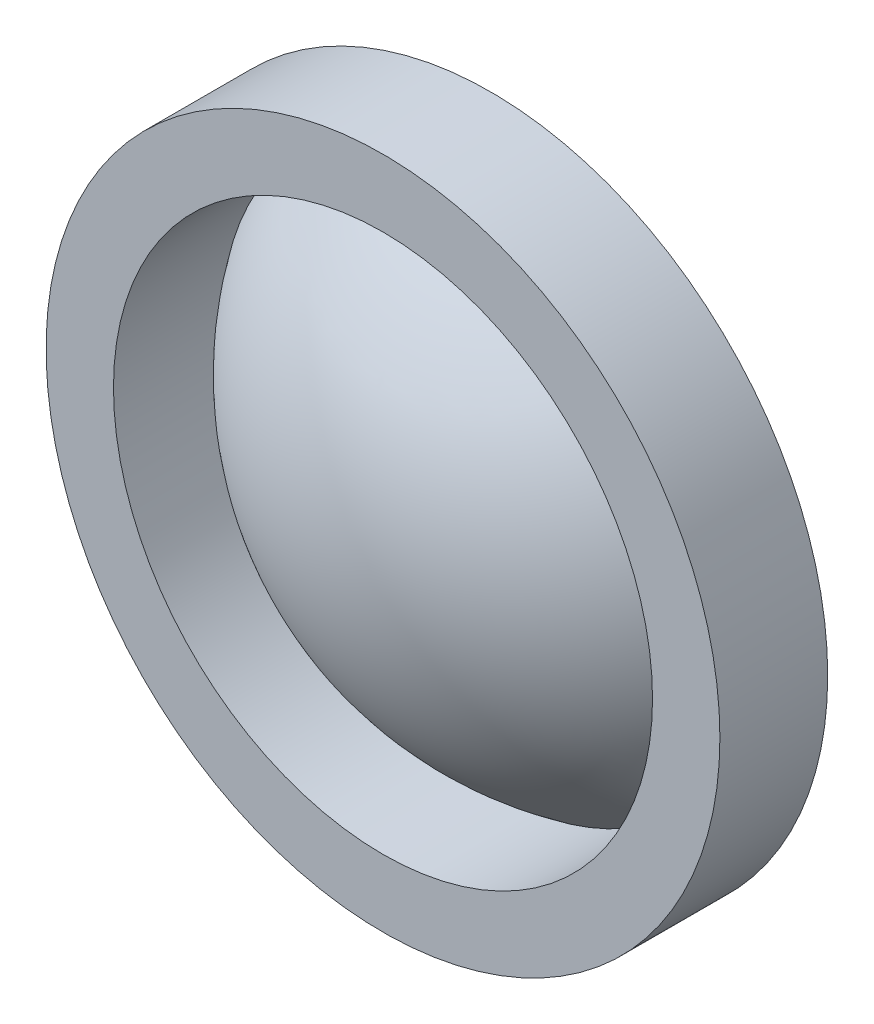
SolidWorks part; units mm, degrees
material "6061 Alloy"
ref_plane "Front" through (0, 0, 0) normal (0, 0, 1) x (1, 0, 0)
ref_plane "Top" through (0, 0, 0) normal (0, 1, 0) x (1, 0, 0)
ref_plane "Right" through (0, 0, 0) normal (1, 0, 0) x (0, 0, -1)
sketch "Sketch2" plane through (0, 0, 0) normal (0, 0, 1) x (1, 0, 0)
  circle A0 centre (0, 0) radius 1000
  circle A1 centre (0, 0) radius 1250
  dimension "D1" = 2000
  dimension "D2" = 2500
extrude "Boss-Extrude1" add sketch "Sketch2" along normal blind 400
sketch "Sketch3" plane through (0, 0, 0) normal (1, 0, 0) x (0, 0, -1)
  line L2 (0, 0) -> (0, -1000)
  line L3 (0, 0) -> (-528.7511, 0)
  line L4 (55, 0) -> (-55, 0) construction
  arc A1 (-528.7511, 0) -> (0, -1000) centre (681.2489, 0) ccw
  dimension "D1" = 1210
revolve "Revolve2" add sketch "Sketch3" angle 360 about L3
